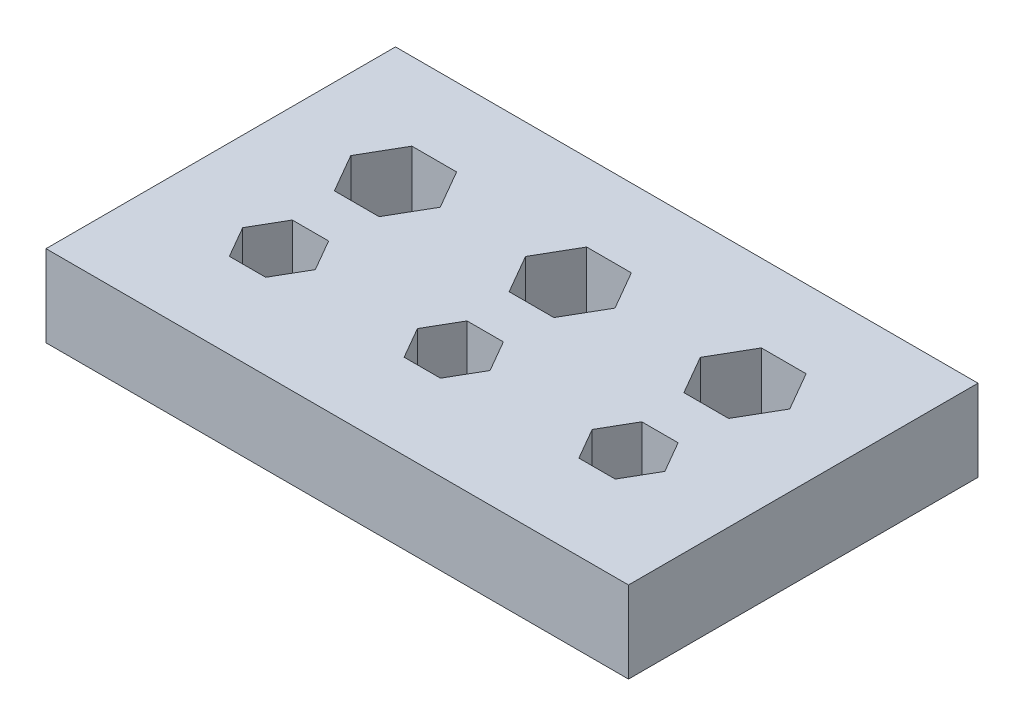
SolidWorks part; units mm, degrees
ref_plane "Front Plane" through (0, 0, 0) normal (0, 0, 1) x (1, 0, 0)
ref_plane "Top Plane" through (0, 0, 0) normal (0, 1, 0) x (1, 0, 0)
ref_plane "Right Plane" through (0, 0, 0) normal (1, 0, 0) x (0, 0, -1)
sketch "Sketch1" plane through (0, 0, 0) normal (0, 1, 0) x (1, 0, 0)
  line L1 (0, 0) -> (63.5, 0)
  line L2 (0, 0) -> (0, 38.1)
  line L3 (0, 38.1) -> (63.5, 38.1)
  line L4 (63.5, 0) -> (63.5, 38.1)
  dimension "D1" = 63.5
  dimension "D2" = 38.1
extrude "Boss-Extrude1" add sketch "Sketch1" along normal blind 8.89
sketch "Sketch2" plane through (0, 8.89, 0) normal (0, 1, 0) x (1, 0, 0)
  line L0 (0, 25.4) -> (63.5, 25.4) construction
  line L1 (0, 38.1) -> (0, 0) construction
  line L2 (63.5, 0) -> (63.5, 38.1) construction
  line L3 (0, 12.7) -> (63.5, 12.7) construction
  line L5 (0, 0) -> (63.5, 0) construction
  line L7 (17.576, 25.4) -> (15.138, 29.6228)
  line L8 (15.138, 29.6228) -> (10.262, 29.6228)
  line L9 (10.262, 29.6228) -> (7.824, 25.4)
  line L10 (7.824, 25.4) -> (10.262, 21.1773)
  line L11 (10.262, 21.1773) -> (15.138, 21.1773)
  line L12 (15.138, 21.1773) -> (17.576, 25.4)
  line L13 (36.626, 25.4) -> (34.188, 29.6228)
  line L14 (34.188, 29.6228) -> (29.312, 29.6228)
  line L15 (29.312, 29.6228) -> (26.874, 25.4)
  line L16 (26.874, 25.4) -> (29.312, 21.1772)
  line L17 (29.312, 21.1772) -> (34.188, 21.1772)
  line L18 (34.188, 21.1772) -> (36.626, 25.4)
  line L19 (55.676, 25.4) -> (53.238, 29.6228)
  line L20 (53.238, 29.6228) -> (48.362, 29.6228)
  line L21 (48.362, 29.6228) -> (45.924, 25.4)
  line L22 (45.924, 25.4) -> (48.362, 21.1772)
  line L23 (48.362, 21.1772) -> (53.238, 21.1772)
  line L24 (53.238, 21.1772) -> (55.676, 25.4)
  line L25 (16.6595, 12.7) -> (14.6797, 16.129)
  line L26 (14.6797, 16.129) -> (10.7203, 16.129)
  line L27 (10.7203, 16.129) -> (8.7405, 12.7)
  line L28 (8.7405, 12.7) -> (10.7203, 9.271)
  line L29 (10.7203, 9.271) -> (14.6797, 9.271)
  line L30 (14.6797, 9.271) -> (16.6595, 12.7)
  line L31 (35.7095, 12.7) -> (33.7297, 16.129)
  line L32 (33.7297, 16.129) -> (29.7703, 16.129)
  line L33 (29.7703, 16.129) -> (27.7905, 12.7)
  line L34 (27.7905, 12.7) -> (29.7703, 9.271)
  line L35 (29.7703, 9.271) -> (33.7297, 9.271)
  line L36 (33.7297, 9.271) -> (35.7095, 12.7)
  line L37 (54.7595, 12.7) -> (52.7797, 16.129)
  line L38 (52.7797, 16.129) -> (48.8203, 16.129)
  line L39 (48.8203, 16.129) -> (46.8405, 12.7)
  line L40 (46.8405, 12.7) -> (48.8203, 9.271)
  line L41 (48.8203, 9.271) -> (52.7797, 9.271)
  line L42 (52.7797, 9.271) -> (54.7595, 12.7)
  circle A0 centre (12.7, 25.4) radius 4.2227 construction
  circle A1 centre (31.75, 25.4) radius 4.2228 construction
  circle A2 centre (50.8, 25.4) radius 4.2227 construction
  circle A3 centre (12.7, 12.7) radius 3.429 construction
  circle A4 centre (31.75, 12.7) radius 3.429 construction
  circle A5 centre (50.8, 12.7) radius 3.429 construction
  circle A6 centre (12.7, 25.4) radius 2.4638
  circle A7 centre (31.75, 25.4) radius 2.4638
  circle A8 centre (50.8, 25.4) radius 2.4638
  circle A9 centre (50.8, 12.7) radius 1.5875
  circle A10 centre (31.75, 12.7) radius 1.5875
  circle A11 centre (12.7, 12.7) radius 1.5875
  dimension "D8" = 3.175
  dimension "D9" = 4.9276
  dimension "D1" = 12.7
  dimension "D2" = 12.7
  dimension "D3" = 6.858
  dimension "D4" = 8.4455
  dimension "D5" = 19.05
  dimension "D6" = 19.05
  dimension "D7" = 12.7
extrude "Cut-Extrude1" cut sketch "Sketch2" against normal blind 7.366
sketch "Sketch3" plane through (0, 8.89, 0) normal (0, 1, 0) x (1, 0, 0)
  circle A0 centre (12.7, 25.4) radius 2.4638 construction
  circle A1 centre (31.75, 25.4) radius 2.4638 construction
  circle A2 centre (50.8, 25.4) radius 2.4638 construction
  circle A3 centre (50.8, 12.7) radius 1.5875 construction
  circle A4 centre (31.75, 12.7) radius 1.5875 construction
  circle A5 centre (12.7, 12.7) radius 1.5875 construction
  circle A6 centre (12.7, 25.4) radius 2.4638
  circle A7 centre (31.75, 25.4) radius 2.4638
  circle A8 centre (50.8, 25.4) radius 2.4638
  circle A9 centre (50.8, 12.7) radius 1.5875
  circle A10 centre (31.75, 12.7) radius 1.5875
  circle A11 centre (12.7, 12.7) radius 1.5875
extrude "Cut-Extrude2" cut sketch "Sketch3" against normal through all
